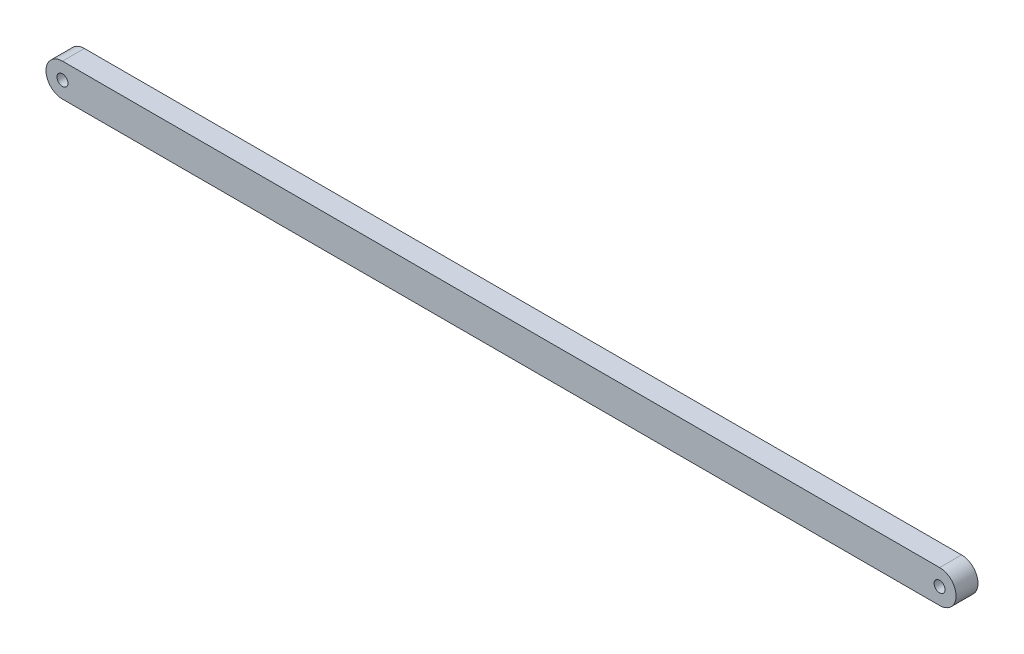
SolidWorks part; units mm, degrees
material "AISI 304"
ref_plane "前视基准面" through (0, 0, 0) normal (0, 0, 1) x (1, 0, 0)
ref_plane "上视基准面" through (0, 0, 0) normal (0, 1, 0) x (1, 0, 0)
ref_plane "右视基准面" through (0, 0, 0) normal (1, 0, 0) x (0, 0, -1)
sketch "草图1" plane through (0, 0, 0) normal (0, 0, 1) x (1, 0, 0)
  line L0 (-50.5402, 31.0783) -> (29.4598, 31.0783)
  line L1 (-50.5402, 28.0783) -> (29.4598, 28.0783)
  circle A0 centre (-50.5402, 29.5783) radius 0.5
  circle A1 centre (29.4598, 29.5783) radius 0.5
  arc A2 (-50.5402, 31.0783) -> (-50.5402, 28.0783) centre (-50.5402, 29.5783) ccw
  arc A3 (29.4598, 28.0783) -> (29.4598, 31.0783) centre (29.4598, 29.5783) ccw
  dimension "D2" = 3
  dimension "D3" = 1
  dimension "D1" = 80
extrude "凸台-拉伸1" add sketch "草图1" along normal blind 2
